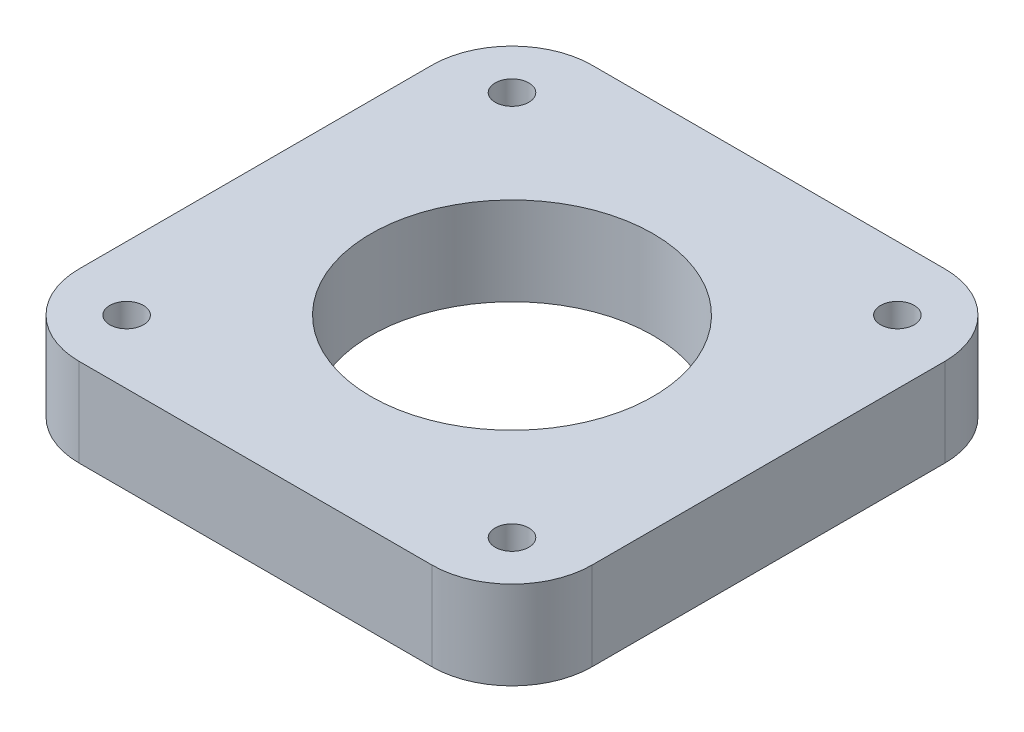
SolidWorks part; units mm, degrees
ref_plane "前视基准面" through (0, 0, 0) normal (0, 0, 1) x (1, 0, 0)
ref_plane "上视基准面" through (0, 0, 0) normal (0, 1, 0) x (1, 0, 0)
ref_plane "右视基准面" through (0, 0, 0) normal (1, 0, 0) x (0, 0, -1)
other "Configuration Table"
sketch "草图1" plane through (0, 0, 0) normal (0, 1, 0) x (1, 0, 0)
  line L1 (-32, -32) -> (32, -32)
  line L2 (-32, -32) -> (-32, 32)
  line L3 (-32, 32) -> (32, 32)
  line L4 (32, -32) -> (32, 32)
  line L5 (-32, -32) -> (32, 32) construction
  line L6 (-32, 32) -> (32, -32) construction
  point P0 (0, 0)
  dimension "D1" = 64
extrude "凸台-拉伸1" add sketch "草图1" along normal blind 11
sketch "草图2" plane through (0, 11, 0) normal (0, 1, 0) x (1, 0, 0)
  line L0 (0, 0) -> (32, 32) construction
  circle A0 centre (0, 0) radius 17.6
  circle A1 centre (0, 0) radius 34 construction
  circle A2 centre (24.0416, 24.0416) radius 2.1
  circle A3 centre (24.0416, -24.0416) radius 2.1
  circle A4 centre (-24.0416, -24.0416) radius 2.1
  circle A5 centre (-24.0416, 24.0416) radius 2.1
  dimension "D1" = 35.2
  dimension "D2" = 68
  dimension "D3" = 4.2
  dimension "D4" = 4
extrude "切除-拉伸1" cut sketch "草图2" against normal blind 11
fillet "圆角1" radius 10 4 edges at (32, 5.5, 32) (-32, 5.5, 32) (32, 5.5, -32) (-32, 5.5, -32)
